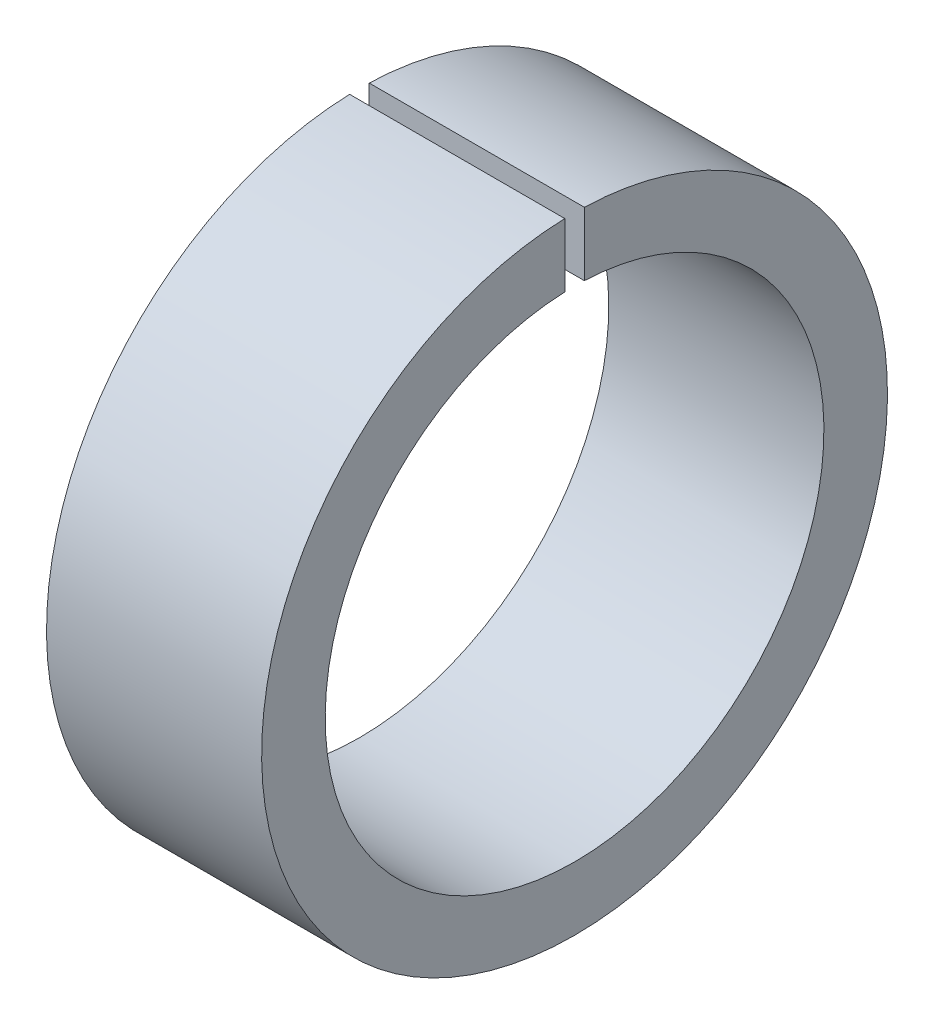
SolidWorks part; units mm, degrees
ref_plane "Piano frontale" through (0, 0, 0) normal (0, 0, 1) x (1, 0, 0)
ref_plane "Piano superiore" through (0, 0, 0) normal (0, 1, 0) x (1, 0, 0)
ref_plane "Piano destro" through (0, 0, 0) normal (1, 0, 0) x (0, 0, -1)
sketch "Schizzo1" plane through (0, 0, 0) normal (1, 0, 0) x (0, 0, -1)
  circle A0 centre (0, 0) radius 16
  circle A1 centre (0, 0) radius 12.75
  dimension "D1" = 32
  dimension "D2" = 25.5
extrude "Estrusione-Estrusione1" add sketch "Schizzo1" along normal blind 11
sketch "Schizzo2" plane through (11, 0, 0) normal (1, 0, 0) x (0, 0, -1)
  line L0 (0, 16) -> (0, 0) construction
  line L2 (-0.5, -3.2677) -> (0.5, -3.2677)
  line L3 (-0.5, -3.2677) -> (-0.5, 16)
  line L4 (-0.5, 16) -> (0.5, 16)
  line L5 (0.5, -3.2677) -> (0.5, 16)
  circle A0 centre (0, 0) radius 16 construction
  dimension "D1" = 1
extrude "Taglio-Estrusione1" cut sketch "Schizzo2" against normal through all
